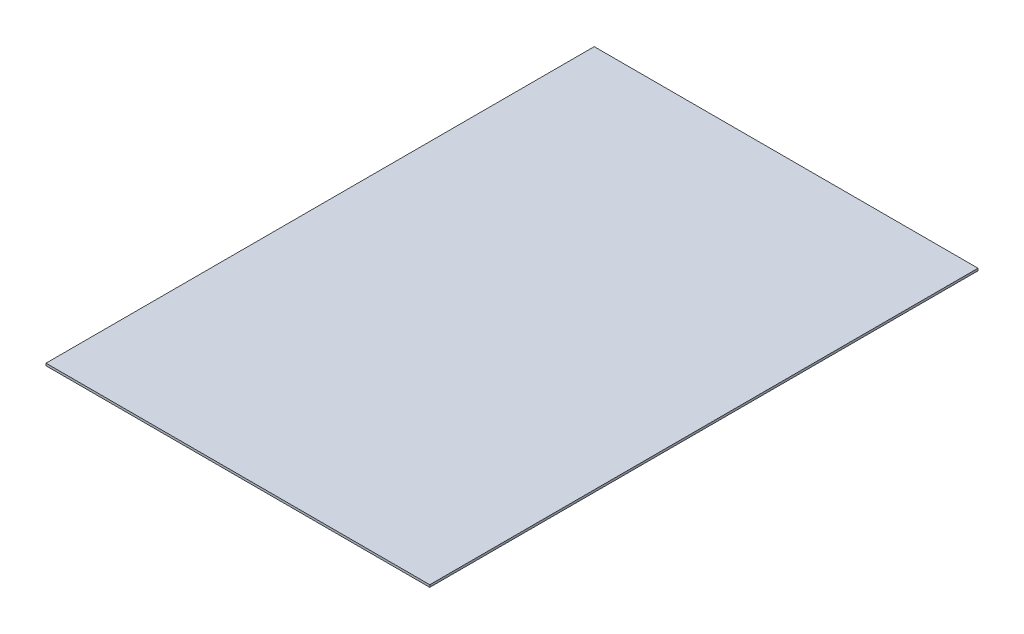
SolidWorks part; units mm, degrees
material "6061-T6 (SS)"
ref_plane "Front Plane" through (0, 0, 0) normal (0, 0, 1) x (1, 0, 0)
ref_plane "Top Plane" through (0, 0, 0) normal (0, 1, 0) x (1, 0, 0)
ref_plane "Right Plane" through (0, 0, 0) normal (1, 0, 0) x (0, 0, -1)
ref_plane "Plane1" through (0, -25.4, 0) normal (0, -1, 0) x (-1, 0, 0)
sketch "Sketch1" plane through (0, -25.4, 0) normal (0, -1, 0) x (-1, 0, 0)
  line L0 (-266.7, -381) -> (-266.7, 0) construction
  line L1 (0, -381) -> (-266.7, -381) construction
  line L7 (-266.7, -381) -> (-266.7, 0)
  line L8 (0, -381) -> (-266.7, -381)
  line L9 (-266.7, 0) -> (-266.7, 381)
  line L10 (-266.7, 381) -> (0, 381)
  line L11 (0, 381) -> (266.7, 381)
  line L12 (266.7, 381) -> (266.7, -381)
  line L13 (266.7, -381) -> (0, -381)
extrude "Boss-Extrude1" add sketch "Sketch1" along normal blind 3.175
